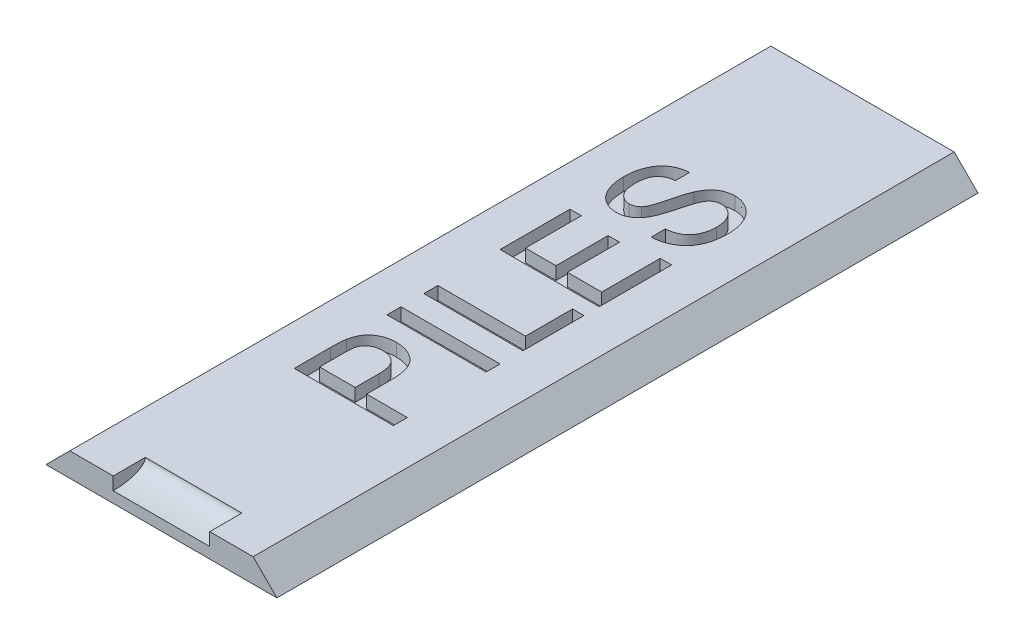
SolidWorks part; units mm, degrees
ref_plane "Alzado" through (0, 0, 0) normal (0, 0, 1) x (1, 0, 0)
ref_plane "Planta" through (0, 0, 0) normal (0, 1, 0) x (1, 0, 0)
ref_plane "Vista lateral" through (0, 0, 0) normal (1, 0, 0) x (0, 0, -1)
sketch "Croquis1" plane through (0, 0, 0) normal (0, 0, 1) x (1, 0, 0)
  line L0 (0, 0) -> (1.85, 1.85)
  line L1 (0, 0) -> (17.95, 0)
  line L2 (16.1, 1.85) -> (17.95, 0)
  line L3 (16.1, 1.85) -> (1.85, 1.85)
  dimension "D1" = 1.85
  dimension "D2" = 45
  dimension "D3" = 17.95
  dimension "D4" = 45
extrude "Saliente-Extruir1" add sketch "Croquis1" along normal blind 54.5
ref_plane "Plano1" through (8.975, 0, 0) normal (1, 0, 0) x (0, 0, -1)
sketch "Croquis3" plane through (8.975, 0, 0) normal (1, 0, 0) x (0, 0, -1)
  line L2 (-54.5, 1.85) -> (0, 1.85) construction
  line L3 (-54.5, 0) -> (-54.5, 1.85) construction
  ellipse E0 centre (-54.5, 1.85) end of major axis (-52, 1.85) minor radius 1
  dimension "D1" = 2.5
  dimension "D2" = 1
extrude "Cortar-Extruir2" cut sketch "Croquis3" against normal mid plane 7.5
sketch "Croquis4" plane through (0, 1.85, 0) normal (0, 1, 0) x (1, 0, 0)
  line L0 (12.725, -52) -> (12.725, 0) construction
  line L1 (16.1, 0) -> (1.85, 0) construction
  text T0 "PILES" font "Arial Narrow" height in points 30
extrude "Cortar-Extruir3" cut sketch "Croquis4" against normal blind 1
